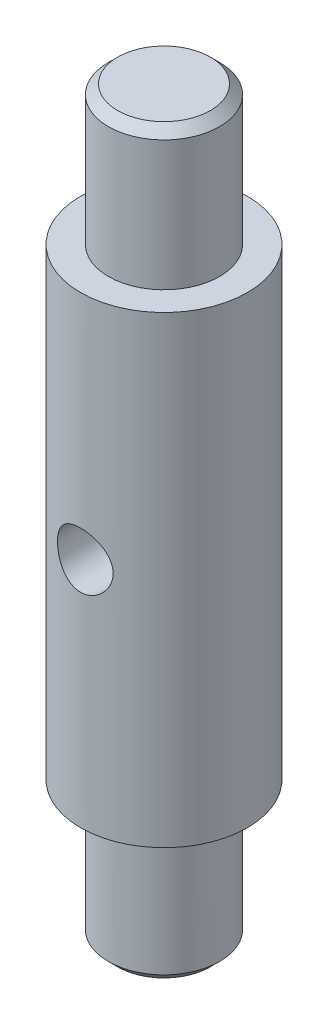
SolidWorks part; units mm, degrees
material "1.1191 (C45E)"
ref_plane "Alzado" through (0, 0, 0) normal (0, 0, 1) x (1, 0, 0)
ref_plane "Planta" through (0, 0, 0) normal (0, 1, 0) x (1, 0, 0)
ref_plane "Vista lateral" through (0, 0, 0) normal (1, 0, 0) x (0, 0, -1)
sketch "Croquis1" plane through (0, 0, 0) normal (0, 0, 1) x (1, 0, 0)
  line L0 (0, 0) -> (0, 15)
  line L1 (0, 15) -> (-3, 15)
  line L2 (-3, 15) -> (-3, 65)
  line L3 (-3, 65) -> (0, 65)
  line L4 (0, 65) -> (0, 80)
  line L5 (0, 80) -> (6, 80)
  line L6 (6, 80) -> (6, 0) construction
  line L7 (6, 0) -> (6, 80)
  line L11 (0, 0) -> (6, 0)
  dimension "D1" = 15
  dimension "D2" = 50
  dimension "D3" = 15
  dimension "D4" = 3
  dimension "D5" = 3
revolve "Revolución1" add sketch "Croquis1" angle 360 about L6
sketch "Croquis2" plane through (0, 0, 0) normal (0, 0, 1) x (1, 0, 0)
  line L0 (6, 15) -> (6, 40) construction
  line L1 (0, 15) -> (12, 15) construction
  circle A0 centre (6, 40) radius 3
  dimension "D1" = 6
extrude "Cortar-Extruir1" cut sketch "Croquis2" against normal through all both and the other way through all
sketch "Croquis3" plane through (0, 0, 0) normal (0, -1, 0) x (1, 0, 0)
  circle A0 centre (6, 0) radius 3
extrude "Cortar-Extruir2" cut sketch "Croquis3" against normal blind 45
chamfer "Chaflán3" distance 1 angle 45 2 edges at (6, 80, 6) (6, 0, 6)
